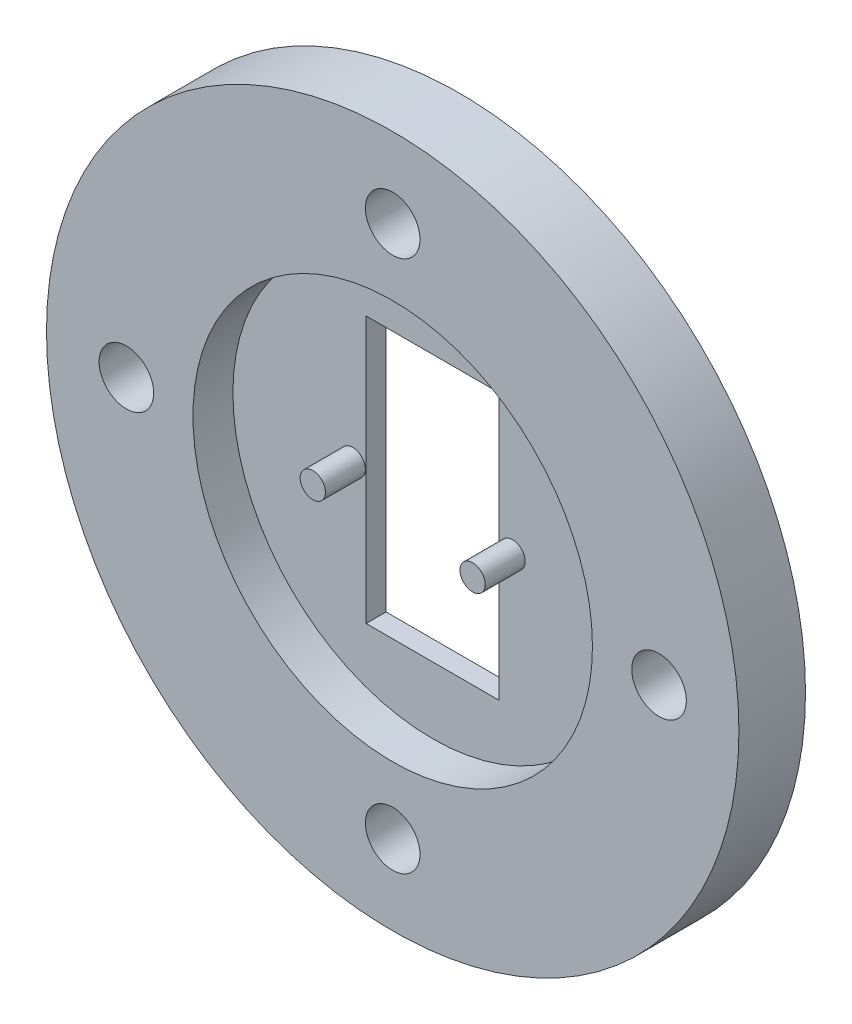
SolidWorks part; units mm, degrees
ref_plane "前视基准面" through (0, 0, 0) normal (0, 0, 1) x (1, 0, 0)
ref_plane "上视基准面" through (0, 0, 0) normal (0, 1, 0) x (1, 0, 0)
ref_plane "右视基准面" through (0, 0, 0) normal (1, 0, 0) x (0, 0, -1)
sketch "草图1" plane through (0, 0, 0) normal (0, 0, 1) x (1, 0, 0)
  circle A0 centre (0, 0) radius 26
  dimension "D1" = 52
extrude "凸台-拉伸1" add sketch "草图1" along normal blind 5
sketch "草图2" plane through (0, 0, 0) normal (0, 0, -1) x (-1, 0, 0)
  line L0 (-20, 0) -> (20, 0) construction
  line L1 (0, 20) -> (0, -20) construction
  circle A0 centre (0, 0) radius 20 construction
  circle A1 centre (0, 20) radius 2.05
  dimension "D1" = 40
  dimension "D2" = 4.1
extrude "切除-拉伸1" cut sketch "草图2" against normal through all
pattern_circular "阵列(圆周)1" count 4 over 360 about axis through (0, 0, 0) along (0, 0, 1) of "切除-拉伸1"
sketch "草图3" plane through (0, 0, 0) normal (0, 0, -1) x (-1, 0, 0)
  circle A0 centre (0, 0) radius 15
  dimension "D1" = 30
extrude "切除-拉伸2" cut sketch "草图3" against normal blind 0.5
sketch "草图4" plane through (0, 0, 5) normal (0, 0, 1) x (1, 0, 0)
  circle A0 centre (0, 0) radius 15
  dimension "D1" = 30
extrude "切除-拉伸3" cut sketch "草图4" against normal offset from surface (3 mm away) 1.5 up to face at (-15, 0, 0.5)
sketch "草图5" plane through (0, 0, 2) normal (0, 0, 1) x (1, 0, 0)
  line L1 (-5, 10) -> (5, 10)
  line L2 (-5, 10) -> (-5, -10)
  line L3 (-5, -10) -> (5, -10)
  line L4 (5, 10) -> (5, -10)
  line L5 (-5, 10) -> (5, -10) construction
  line L6 (-5, -10) -> (5, 10) construction
  point P0 (0, 0)
  dimension "D1" = 10
  dimension "D2" = 20
extrude "切除-拉伸4" cut sketch "草图5" against normal through all contours L2 L1 L4 L3
sketch "草图6" plane through (0, 0, 2) normal (0, 0, 1) x (1, 0, 0)
  circle A0 centre (-6, 0) radius 0.95
  dimension "D2" = 1.9
  dimension "D1" = 6
extrude "凸台-拉伸2" add sketch "草图6" along normal blind 3
mirror "镜向1" about plane through (0, 0, 0) normal (1, 0, 0) of "凸台-拉伸2"
